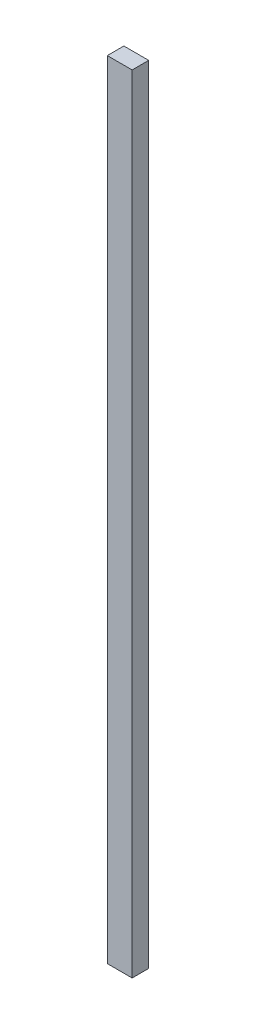
SolidWorks part; units mm, degrees
ref_plane "Front Plane" through (0, 0, 0) normal (0, 0, 1) x (1, 0, 0)
ref_plane "Top Plane" through (0, 0, 0) normal (0, 1, 0) x (1, 0, 0)
ref_plane "Right Plane" through (0, 0, 0) normal (1, 0, 0) x (0, 0, -1)
sketch "Sketch1" plane through (0, 0, -38.1) normal (0, 0, -1) x (-1, 0, 0)
  line L0 (-29, 224.6315) -> (29, 224.6315) construction
  line L1 (-6, 604.1315) -> (6, 604.1315)
  line L2 (-6, 604.1315) -> (-6, 224.6315)
  line L3 (-6, 224.6315) -> (6, 224.6315)
  line L4 (6, 604.1315) -> (6, 224.6315)
  line L5 (-6, 604.1315) -> (6, 224.6315) construction
  line L6 (-6, 224.6315) -> (6, 604.1315) construction
  line L7 (-29, 224.6315) -> (29, 224.6315) construction
  line L8 (-29, 604.1315) -> (29, 604.1315) construction
  line L9 (-29, 604.1315) -> (29, 604.1315) construction
  line L10 (0, 604.1315) -> (0, 224.6315) construction
  point P0 (0, 414.3815)
  dimension "D1" = 12
extrude "Boss-Extrude1" add sketch "Sketch1" along normal blind 8
